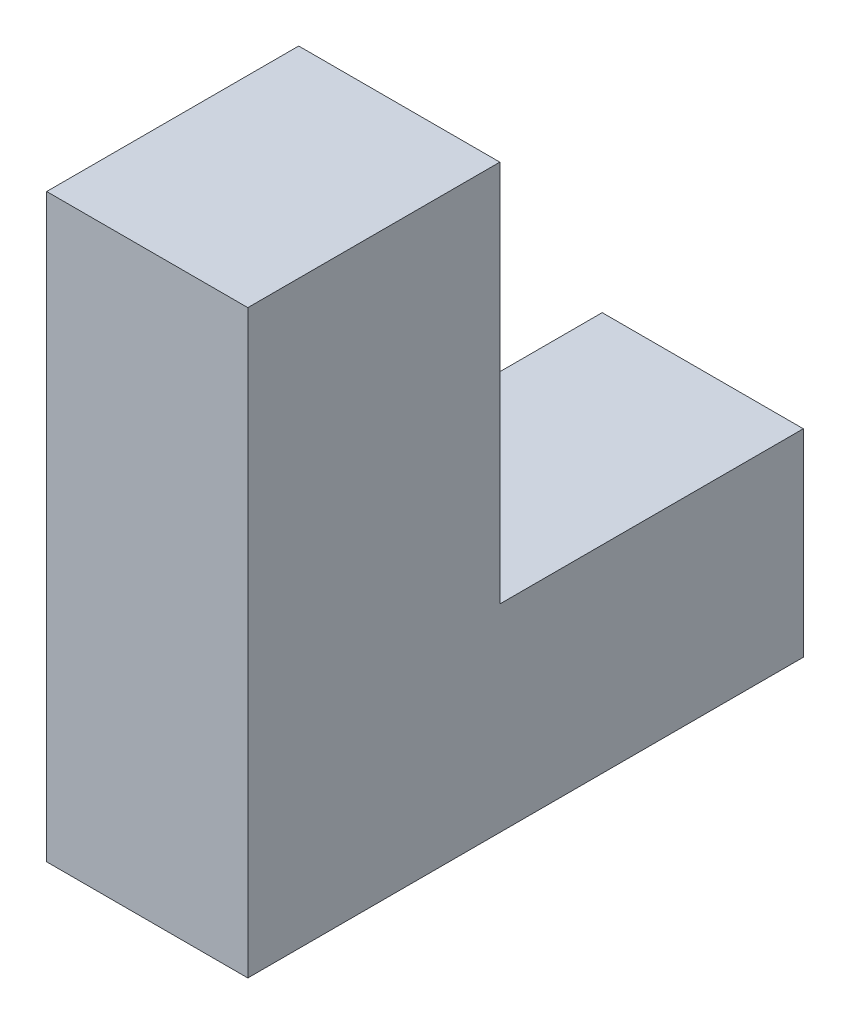
SolidWorks part; units mm, degrees
ref_plane "Спереди" through (0, 0, 0) normal (0, 0, 1) x (1, 0, 0)
ref_plane "Сверху" through (0, 0, 0) normal (0, 1, 0) x (1, 0, 0)
ref_plane "Справа" through (0, 0, 0) normal (1, 0, 0) x (0, 0, -1)
sketch "Эскиз1" plane through (0, 0, 0) normal (1, 0, 0) x (0, 0, -1)
  line L0 (0, -14.695) -> (0, 43.0353)
  line L1 (0, 43.0353) -> (25.0602, 43.0353)
  line L2 (25.0602, 43.0353) -> (25.0602, 4.9858)
  line L3 (25.0602, 4.9858) -> (55.2374, 4.9858)
  line L4 (55.2374, 4.9858) -> (55.2374, -14.695)
  line L5 (55.2374, -14.695) -> (0, -14.695)
extrude "Бобышка-Вытянуть1" add sketch "Эскиз1" along normal mid plane 20
ref_plane "face_for_mating" through (0, 0, 0) normal (0, 0, 1) x (1, 0, 0)
ref_plane "face_for_horizont" through (0, -14.695, 0) normal (0, -1, 0) x (1, 0, 0)
